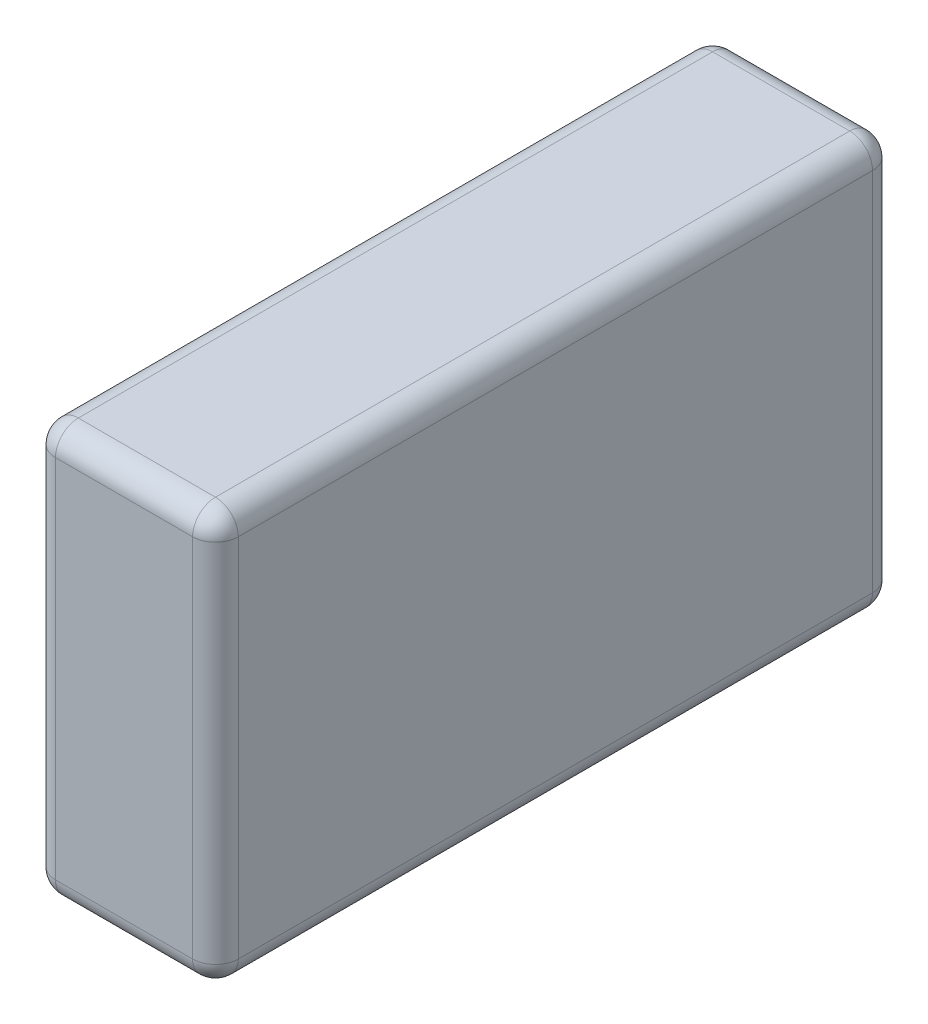
SolidWorks part; units mm, degrees
ref_plane "前视基准面" through (0, 0, 0) normal (0, 0, 1) x (1, 0, 0)
ref_plane "上视基准面" through (0, 0, 0) normal (0, 1, 0) x (1, 0, 0)
ref_plane "右视基准面" through (0, 0, 0) normal (1, 0, 0) x (0, 0, -1)
other "Configuration Table"
sketch "草图1" plane through (0, 0, 0) normal (1, 0, 0) x (0, 0, -1)
  line L1 (-59, 36) -> (60, 36)
  line L2 (-59, 36) -> (-59, -36)
  line L3 (-59, -36) -> (60, -36)
  line L4 (60, 36) -> (60, -36)
  dimension "D1" = 72
  dimension "D2" = 119
  dimension "D3" = 60
  dimension "D4" = 36
extrude "凸台-拉伸1" add sketch "草图1" along normal blind 32
fillet "圆角1" radius 4 12 edges at (16, -36, -60) (0, -36, -0.5) (0, 0, -60) (16, -36, 59) (0, 0, 59) (32, 0, -60) (32, -36, -0.5) (32, 0, 59) (16, 36, -60) (32, 36, -0.5) (16, 36, 59) (0, 36, -0.5)
